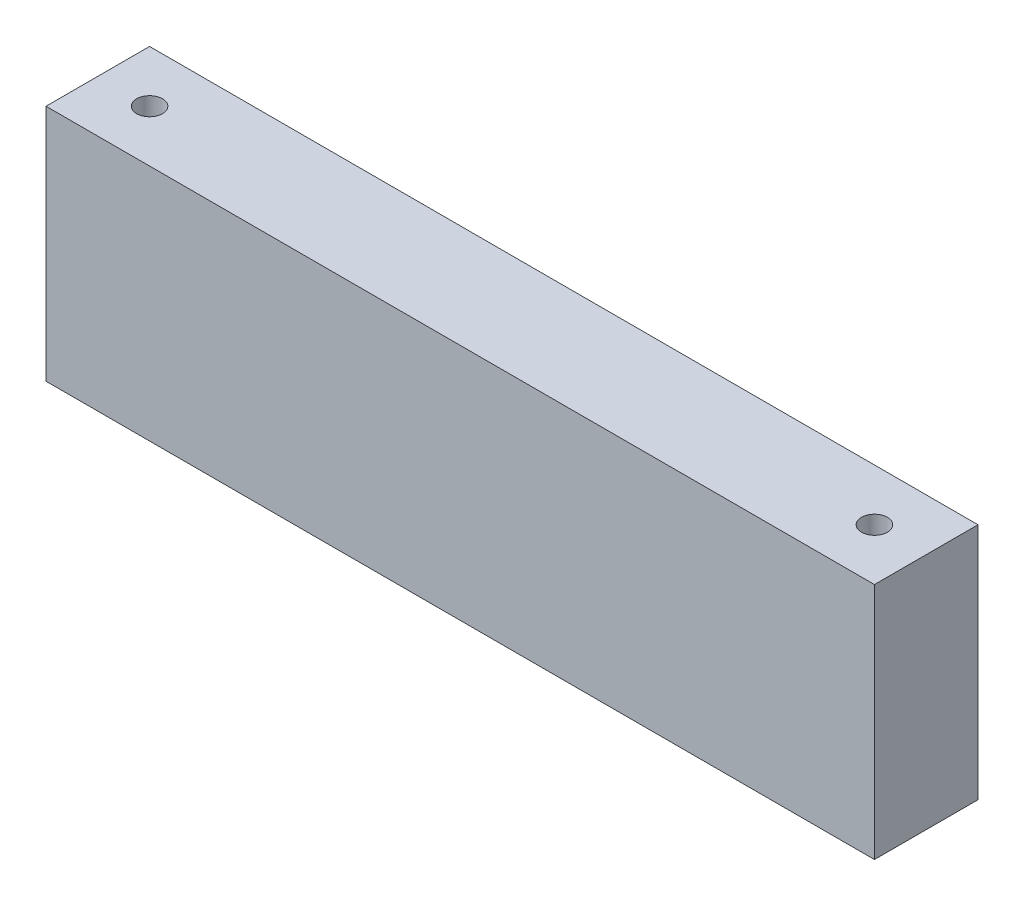
SolidWorks part; units mm, degrees
ref_plane "Front Plane" through (0, 0, 0) normal (0, 0, 1) x (1, 0, 0)
ref_plane "Top Plane" through (0, 0, 0) normal (0, 1, 0) x (1, 0, 0)
ref_plane "Right Plane" through (0, 0, 0) normal (1, 0, 0) x (0, 0, -1)
sketch "Sketch1" plane through (0, 0, 0) normal (0, 0, 1) x (1, 0, 0)
  line L1 (-50.8, -14.605) -> (50.8, -14.605)
  line L2 (-50.8, -14.605) -> (-50.8, 14.605)
  line L3 (-50.8, 14.605) -> (50.8, 14.605)
  line L4 (50.8, -14.605) -> (50.8, 14.605)
  line L5 (-50.8, -14.605) -> (50.8, 14.605) construction
  line L6 (-50.8, 14.605) -> (50.8, -14.605) construction
  point P0 (0, 0)
  dimension "D1" = 29.21
  dimension "D2" = 101.6
extrude "Boss-Extrude1" add sketch "Sketch1" along normal blind 12.7
sketch "Sketch2" plane through (0, 14.605, 0) normal (0, 1, 0) x (1, 0, 0)
  line L0 (-50.8, -6.35) -> (50.8, -6.35) construction
  line L1 (-50.8, -12.7) -> (-50.8, 0) construction
  line L2 (50.8, -12.7) -> (50.8, 0) construction
  circle A0 centre (-44.45, -6.35) radius 1.5875
  circle A1 centre (44.45, -6.35) radius 1.5875
  dimension "D1" = 3.175
  dimension "D2" = 6.35
  dimension "D3" = 6.35
extrude "Cut-Extrude1" cut sketch "Sketch2" against normal through all
